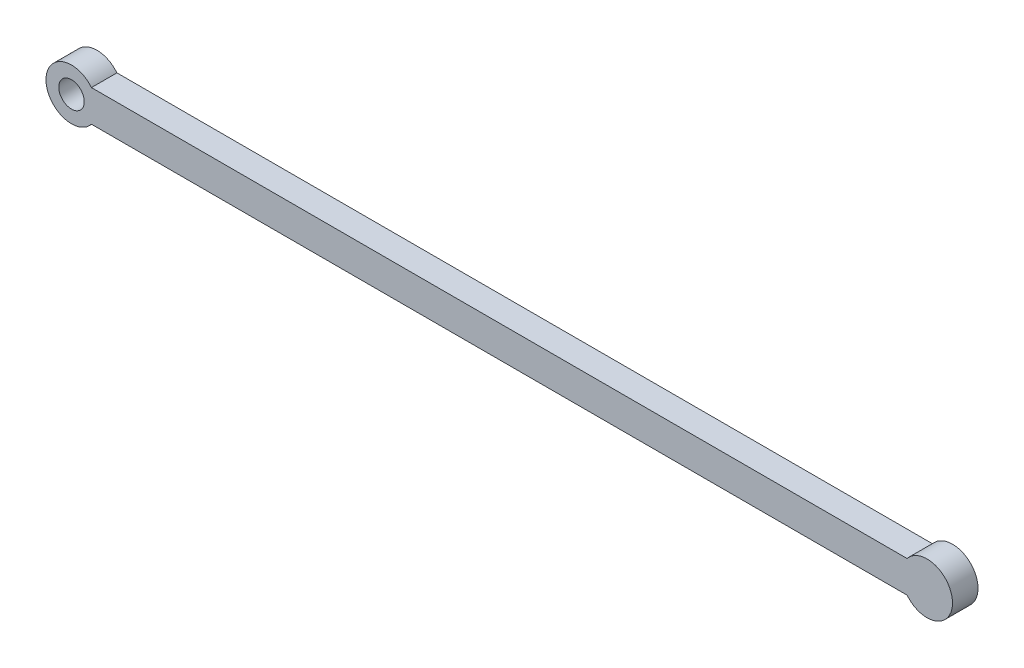
SolidWorks part; units mm, degrees
ref_plane "Front Plane" through (0, 0, 0) normal (0, 0, 1) x (1, 0, 0)
ref_plane "Top Plane" through (0, 0, 0) normal (0, 1, 0) x (1, 0, 0)
ref_plane "Right Plane" through (0, 0, 0) normal (1, 0, 0) x (0, 0, -1)
sketch "Sketch1" plane through (0, 0, 0) normal (0, 0, 1) x (1, 0, 0)
  line L0 (3.9122, 3.1136) -> (163.9122, 3.1136)
  line L1 (0, 0) -> (0.3865, 0) construction
  line L2 (3.9122, -3.1136) -> (163.9122, -3.1136)
  line L3 (83.9122, 3.1136) -> (83.9122, -9.4723) construction
  circle A0 centre (0, 0) radius 2.5
  arc A1 (3.9122, 3.1136) -> (3.9122, -3.1136) centre (0, 0) ccw
  arc A2 (163.9122, 3.1136) -> (163.9122, -3.1136) centre (167.8244, 0) cw
  dimension "D1" = 5
  dimension "D2" = 10
  dimension "D3" = 160
extrude "Boss-Extrude1" add sketch "Sketch1" along normal blind 5
sketch "Sketch3" plane through (0, 0, 0) normal (0, 0, -1) x (-1, 0, 0)
  circle A0 centre (-167.8244, 0) radius 0.1
  dimension "D1" = 0.2
extrude "Boss-Extrude2" add sketch "Sketch3" along normal blind 0.1
